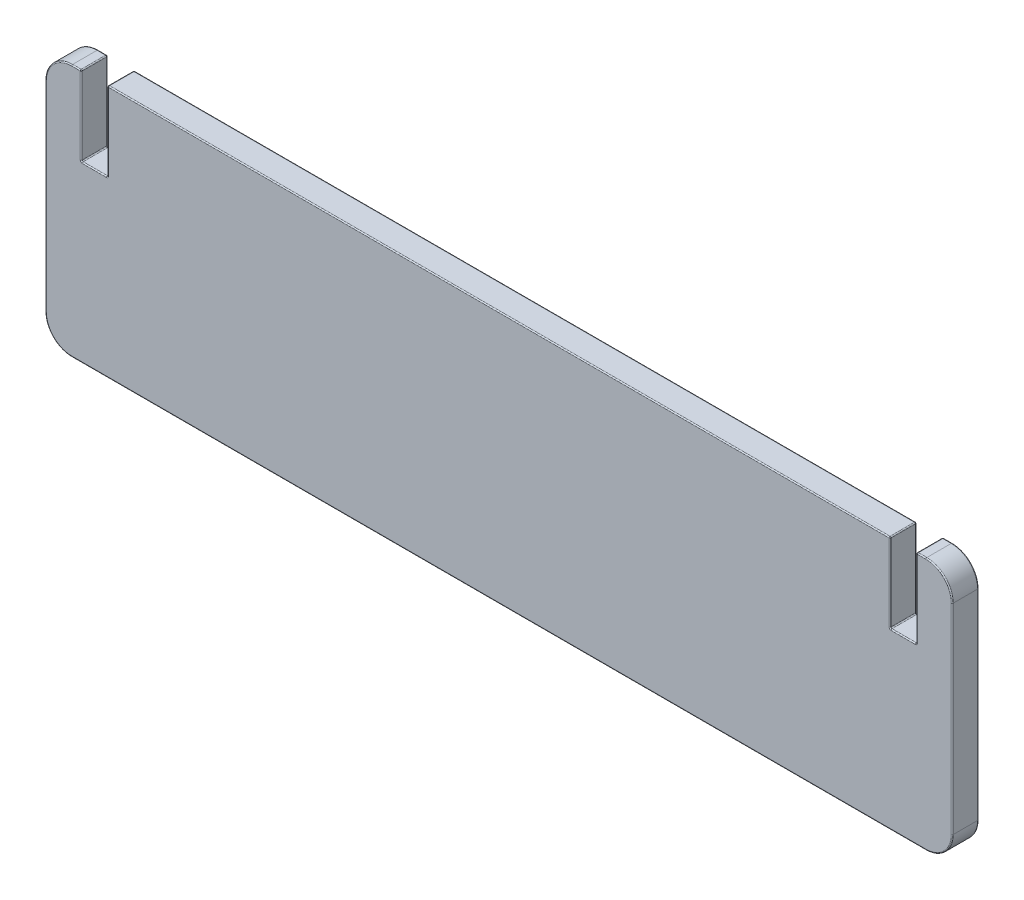
SolidWorks part; units mm, degrees
ref_plane "Plano frontal" through (0, 0, 0) normal (0, 0, 1) x (1, 0, 0)
ref_plane "Plano superior" through (0, 0, 0) normal (0, 1, 0) x (1, 0, 0)
ref_plane "Plano direito" through (0, 0, 0) normal (1, 0, 0) x (0, 0, -1)
sketch "Esboço1" plane through (0, 0, 0) normal (0, 0, 1) x (1, 0, 0)
  line L54 (3.3229, 140.3383) -> (84.3229, 140.3383)
  line L55 (0.8229, 142.8383) -> (0.8229, 161.8383)
  line L56 (3.3229, 164.3383) -> (84.3229, 164.3383)
  line L57 (86.8229, 142.8383) -> (86.8229, 161.8383)
  line L58 (6.7229, 164.3383) -> (4.2229, 164.3383)
  line L59 (6.7229, 164.3383) -> (6.7229, 156.8383)
  line L60 (6.7229, 156.8383) -> (4.2229, 156.8383)
  line L61 (4.2229, 164.3383) -> (4.2229, 156.8383)
  line L62 (83.4229, 164.3383) -> (80.9229, 164.3383)
  line L63 (83.4229, 164.3383) -> (83.4229, 156.8383)
  line L64 (83.4229, 156.8383) -> (80.9229, 156.8383)
  line L65 (80.9229, 164.3383) -> (80.9229, 156.8383)
  arc A12 (84.3229, 140.3383) -> (86.8229, 142.8383) centre (84.3229, 142.8383) ccw
  arc A13 (84.3229, 164.3383) -> (86.8229, 161.8383) centre (84.3229, 161.8383) cw
  arc A14 (0.8229, 161.8383) -> (3.3229, 164.3383) centre (3.3229, 161.8383) cw
  arc A15 (3.3229, 140.3383) -> (0.8229, 142.8383) centre (3.3229, 142.8383) cw
  point P110 (43.8229, 164.3383)
  dimension "D31" = 2.5
  dimension "D32" = 2.5
  dimension "D33" = 7.5
  dimension "D34" = 74.2
  dimension "D35" = 37.1
extrude "Ressalto-extrusão1" add sketch "Esboço1" along normal blind 2.5 contours A15 L54 A12 L57 A13 L56 L63 L64 L65 L59 L60 L61 A14 L55
fillet "Filete1" radius 0.1 40 edges at (83.4229, 164.3383, 1.25) (83.4229, 156.8383, 1.25) (80.9229, 156.8383, 1.25) (80.9229, 164.3383, 1.25) (6.7229, 164.3383, 1.25) (6.7229, 156.8383, 1.25) (4.2229, 156.8383, 1.25) (4.2229, 164.3383, 1.25) (0.8229, 152.3383, 2.5) (1.5551, 163.6061, 2.5) (3.7729, 164.3383, 2.5) (4.2229, 160.5883, 2.5) (5.4729, 156.8383, 2.5) (6.7229, 160.5883, 2.5) (43.8229, 164.3383, 2.5) (80.9229, 160.5883, 2.5) (82.1729, 156.8383, 2.5) (83.4229, 160.5883, 2.5) (83.8729, 164.3383, 2.5) (86.0906, 163.6061, 2.5) (86.8229, 152.3383, 2.5) (86.0906, 141.0706, 2.5) (43.8229, 140.3383, 2.5) (1.5551, 141.0706, 2.5) (43.8229, 140.3383, 0) (86.0906, 141.0706, 0) (86.8229, 152.3383, 0) (86.0906, 163.6061, 0) (83.8729, 164.3383, 0) (83.4229, 160.5883, 0) (82.1729, 156.8383, 0) (80.9229, 160.5883, 0) (43.8229, 164.3383, 0) (6.7229, 160.5883, 0) (5.4729, 156.8383, 0) (4.2229, 160.5883, 0) (3.7729, 164.3383, 0) (1.5551, 163.6061, 0) (0.8229, 152.3383, 0) (1.5551, 141.0706, 0)
